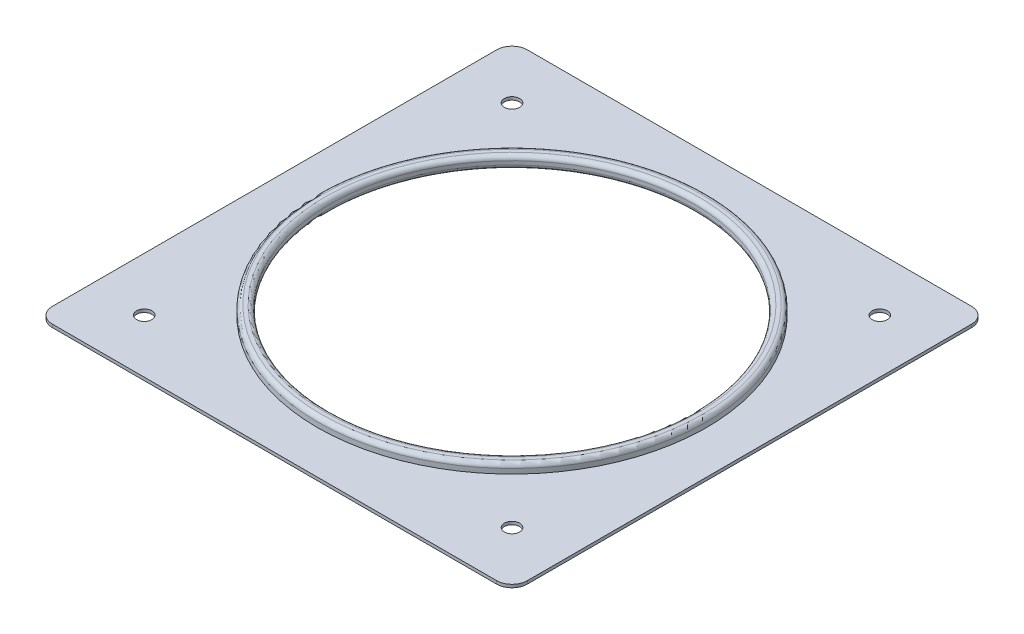
SolidWorks part; units mm, degrees
ref_plane "Front Plane" through (0, 0, 0) normal (0, 0, 1) x (1, 0, 0)
ref_plane "Top Plane" through (0, 0, 0) normal (0, 1, 0) x (1, 0, 0)
ref_plane "Right Plane" through (0, 0, 0) normal (1, 0, 0) x (0, 0, -1)
sketch "Sketch1" plane through (0, 0, 0) normal (0, 1, 0) x (1, 0, 0)
  line L1 (-72.5, -77.5) -> (72.5, -77.5)
  line L2 (-77.5, -72.5) -> (-77.5, 72.5)
  line L3 (-72.5, 77.5) -> (72.5, 77.5)
  line L4 (77.5, -72.5) -> (77.5, 72.5)
  line L5 (-77.5, -77.5) -> (77.5, 77.5) construction
  line L6 (-77.5, 77.5) -> (77.5, -77.5) construction
  line L7 (-60, -60) -> (60, -60) construction
  line L8 (-60, -60) -> (-60, 60) construction
  line L9 (-60, 60) -> (60, 60) construction
  line L10 (60, -60) -> (60, 60) construction
  line L11 (-60, -60) -> (60, 60) construction
  line L12 (-60, 60) -> (60, -60) construction
  circle A0 centre (0, 0) radius 59.5
  circle A1 centre (-60, 60) radius 2.5
  circle A2 centre (60, 60) radius 2.5
  circle A3 centre (60, -60) radius 2.5
  circle A4 centre (-60, -60) radius 2.5
  arc A5 (-77.5, -72.5) -> (-72.5, -77.5) centre (-72.5, -72.5) ccw
  arc A6 (72.5, -77.5) -> (77.5, -72.5) centre (72.5, -72.5) ccw
  arc A7 (77.5, 72.5) -> (72.5, 77.5) centre (72.5, 72.5) ccw
  arc A8 (-72.5, 77.5) -> (-77.5, 72.5) centre (-72.5, 72.5) ccw
  point P21 (0, 0)
  dimension "D1" = 155
  dimension "D2" = 119
  dimension "D3" = 5
  dimension "D5" = 5
  dimension "D4" = 4
extrude "Boss-Extrude1" add sketch "Sketch1" along normal blind 1
sketch "Sketch2" plane through (0, 1, 0) normal (0, 1, 0) x (1, 0, 0)
  circle A0 centre (0, 0) radius 59.5
  circle A1 centre (0, 0) radius 63.5
  dimension "D1" = 4
extrude "Boss-Extrude2" add sketch "Sketch2" along normal blind 3
fillet "Fillet1" radius 1.4 2 edges at (0, 4, 59.5) (0, 4, 63.5)
fillet "Fillet2" radius 1.4 1 edges at (0, 0, 59.5)
